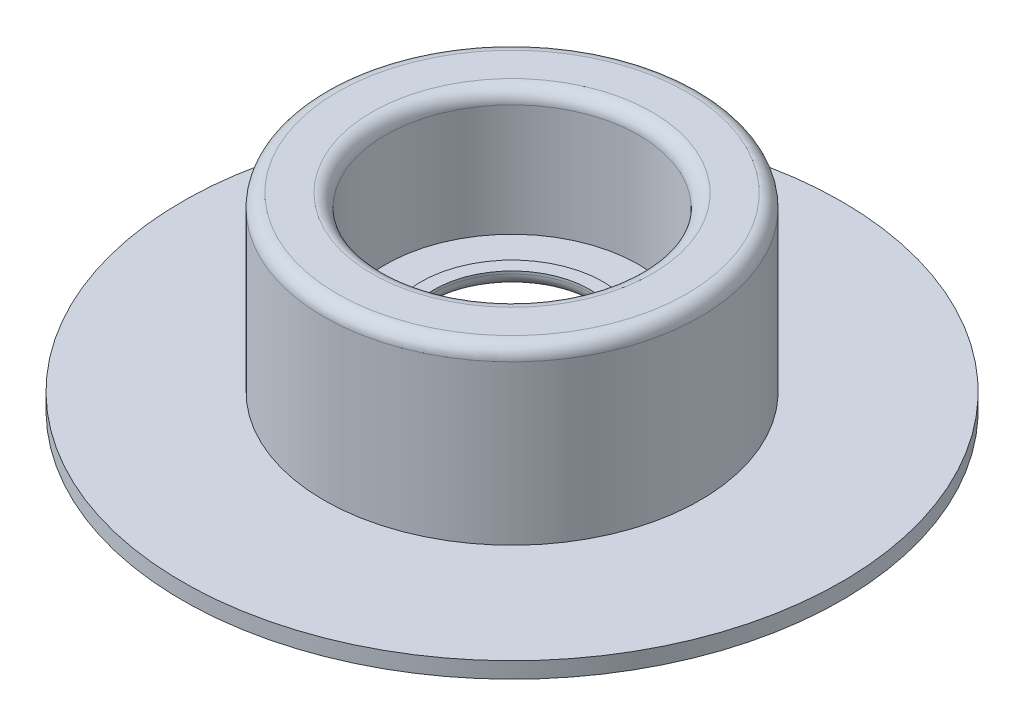
SolidWorks part; units mm, degrees
material "Brass"
ref_plane "Front Plane" through (0, 0, 0) normal (0, 0, 1) x (1, 0, 0)
ref_plane "Top Plane" through (0, 0, 0) normal (0, 1, 0) x (1, 0, 0)
ref_plane "Right Plane" through (0, 0, 0) normal (1, 0, 0) x (0, 0, -1)
sketch "Sketch1" plane through (0, 0, 0) normal (0, 0, 1) x (1, 0, 0)
  line L0 (-6.2738, 0) -> (-3.175, 0)
  line L1 (0, 0) -> (0, 42.4313) construction
  line L2 (-6.2738, 0) -> (-6.2738, 0.3048)
  line L3 (-6.2738, 0.3048) -> (-3.5814, 0.3048)
  line L4 (-3.5814, 0.3048) -> (-3.5814, 3.5814)
  line L5 (-3.5814, 3.5814) -> (-2.413, 3.5814)
  line L6 (-1.4859, 1.2446) -> (-1.7399, 1.2446)
  line L7 (-3.175, 0) -> (-3.175, 3.2766)
  line L8 (-1.7399, 1.2446) -> (-1.7399, 1.1938)
  line L10 (-3.175, 3.2766) -> (-2.8702, 3.2766)
  line L11 (-2.8702, 3.2766) -> (-2.8702, 0.9398)
  line L12 (-2.8702, 0.9398) -> (-1.4859, 0.9398)
  line L13 (-1.4859, 0.9398) -> (-1.4859, 1.2446)
  line L14 (-1.7399, 1.1938) -> (-2.413, 1.1938)
  line L15 (-2.413, 1.1938) -> (-2.413, 3.5814)
  dimension "D1" = 12.5476
  dimension "D2" = 0.3048
  dimension "D3" = 6.35
  dimension "D4" = 1.1684
  dimension "D5" = 7.1628
  dimension "D6" = 2.9718
  dimension "D7" = 0.9398
  dimension "D8" = 3.5814
  dimension "D9" = 0.254
  dimension "D10" = 0.3048
  dimension "D11" = 0.254
revolve "Revolve1" add sketch "Sketch1" angle 360 about L1
fillet "Fillet1" radius 0.254 5 edges at (0, 3.5814, -3.5814) (0, 3.5814, -2.413) (0, 0, -3.175) (0, 0.9398, -2.8702) (0, 0.9398, -1.4859)
